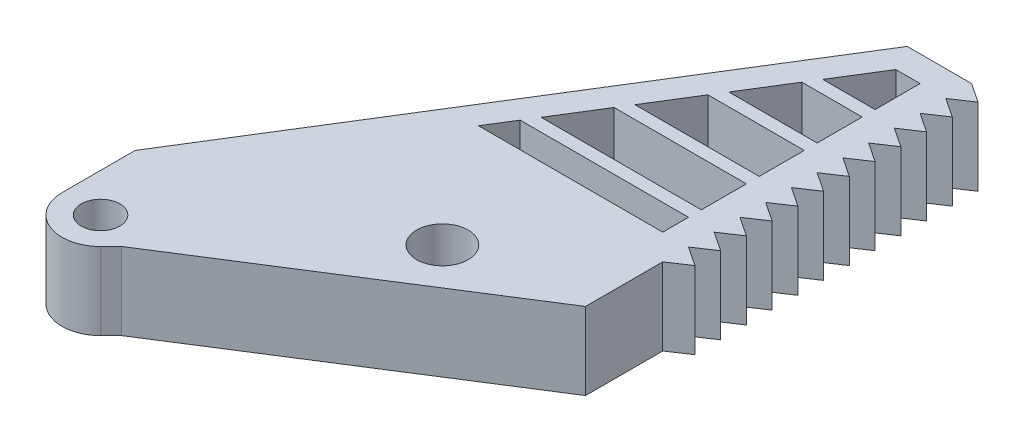
SolidWorks part; units mm, degrees
ref_plane "前视基准面" through (0, 0, 0) normal (0, 0, 1) x (1, 0, 0)
ref_plane "上视基准面" through (0, 0, 0) normal (0, 1, 0) x (1, 0, 0)
ref_plane "右视基准面" through (0, 0, 0) normal (1, 0, 0) x (0, 0, -1)
sketch "草图1" plane through (0, 0, 0) normal (0, 1, 0) x (1, 0, 0)
  line L0 (0, 0) -> (-5, 0)
  line L1 (-5, 0) -> (-28, -37)
  line L2 (-28, -37) -> (-28, -50)
  line L5 (0, -30) -> (0, 0)
  line L6 (-28, -50) -> (-22.0788, -44)
  line L7 (-22.0788, -44) -> (0, -30)
  dimension "D1" = 50
  dimension "D2" = 13
  dimension "D3" = 13
  dimension "D4" = 30
  dimension "D5" = 28
  dimension "D6" = 5
  dimension "D7" = 6
extrude "凸台-拉伸1" add sketch "草图1" along normal blind 6
sketch "草图2" plane through (0, 6, 0) normal (0, 1, 0) x (1, 0, 0)
  line L0 (-3.8883, -2) -> (-2, -2)
  line L1 (-2, -2) -> (-2, -22)
  line L3 (-16.3208, -22) -> (-3.8883, -2)
  line L4 (-5, 0) -> (-28, -37) construction
  line L5 (0, 0) -> (-5, 0) construction
  line L6 (0, -30) -> (0, 0) construction
  line L8 (-2, -22) -> (-16.3208, -22)
  dimension "D1" = 2
  dimension "D2" = 2
  dimension "D3" = 2
  dimension "D4" = 8
extrude "切除-拉伸1" cut sketch "草图2" against normal through all
sketch "草图3" plane through (0, 6, 0) normal (0, 1, 0) x (1, 0, 0)
  line L0 (-6.6856, -6.5) -> (-2, -6.5)
  line L1 (-3.8883, -2) -> (-16.3208, -22) construction
  line L2 (-2, -22) -> (-2, -2) construction
  line L3 (-9.4829, -11) -> (-2, -11)
  line L4 (-12.2802, -15.5) -> (-2, -15.5)
  line L5 (-15.0775, -20) -> (-2, -20)
  line L6 (-2, -2) -> (-3.8883, -2) construction
  dimension "D1" = 4.5
  dimension "D2" = 4.5
  dimension "D3" = 4.5
  dimension "D4" = 4.5
extrude "拉伸-薄壁1" add sketch "草图3" against normal up to surface (6 mm away) thin up to face at (-6.0523, 0, 12) thin type one direction reverse wall 1
sketch "草图4" plane through (0, 6, 0) normal (0, 1, 0) x (1, 0, 0)
  line L0 (0, 0) -> (1.5, -1)
  line L1 (1.5, -1) -> (0, -2)
  line L2 (0, -30) -> (0, 0) construction
  line L3 (0, -2) -> (0, 0)
  line L4 (1.5, -1) -> (0, -1) construction
  dimension "D1" = 1.5
  dimension "D2" = 2
extrude "凸台-拉伸2" add sketch "草图4" against normal blind 6
pattern_linear "阵列(线性)1" count 12 spacing 2 along (0, 0, 1) of "凸台-拉伸2"
fillet "圆角3" radius 3 1 edges at (-28, 3, 50)
sketch "草图5" plane through (0, 6, 0) normal (0, 1, 0) x (1, 0, 0)
  line L0 (-25, -42.6891) -> (-9.7047, -31.4173) construction
  line L4 (-22.0788, -44) -> (0, -30) construction
  circle A0 centre (-25, -42.6891) radius 1.5
  circle A1 centre (-9.7047, -31.4173) radius 2
  arc A2 (-28, -42.6891) -> (-22.8647, -44.7964) centre (-25, -42.6891) ccw construction
  dimension "D1" = 3
  dimension "D2" = 4
  dimension "D4" = 4
  dimension "D3" = 19
extrude "切除-拉伸2" cut sketch "草图5" against normal through all
